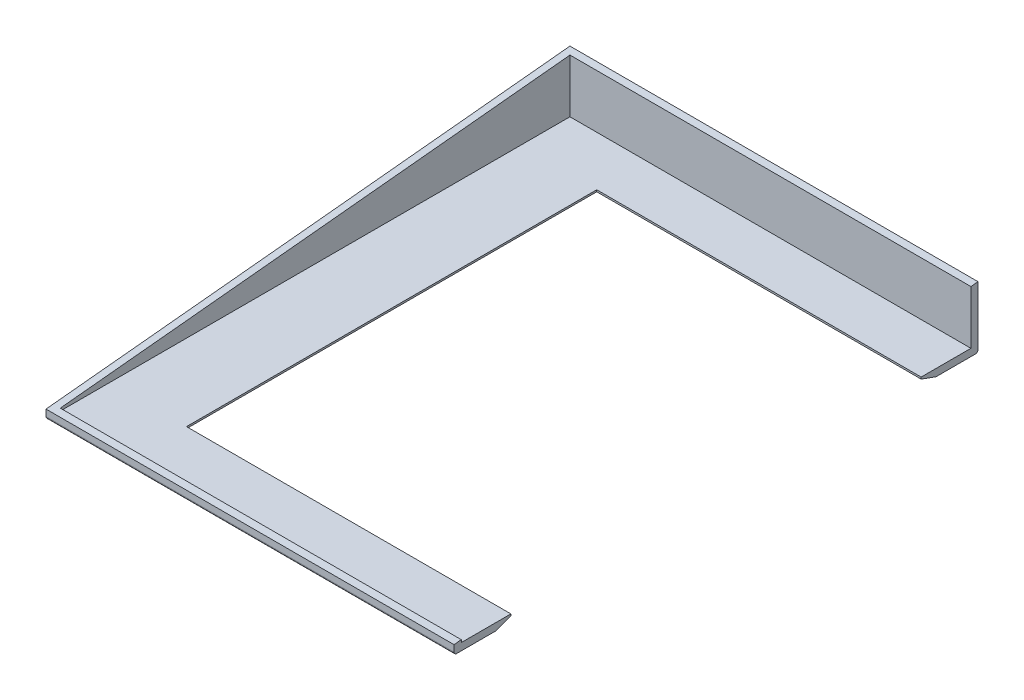
SolidWorks part; units mm, degrees
ref_plane "Alzado" through (0, 0, 0) normal (0, 0, 1) x (1, 0, 0)
ref_plane "Planta" through (0, 0, 0) normal (0, 1, 0) x (1, 0, 0)
ref_plane "Vista lateral" through (0, 0, 0) normal (1, 0, 0) x (0, 0, -1)
sketch "Croquis1" plane through (0, 0, 0) normal (0, 1, 0) x (1, 0, 0)
  line L1 (-110.2037, -69.6794) -> (110.2037, -69.6794)
  line L2 (-110.2037, -69.6794) -> (-110.2037, 69.6794)
  line L3 (-110.2037, 69.6794) -> (110.2037, 69.6794)
  line L4 (110.2037, -69.6794) -> (110.2037, 69.6794)
  line L5 (-110.2037, -69.6794) -> (110.2037, 69.6794) construction
  line L6 (-110.2037, 69.6794) -> (110.2037, -69.6794) construction
  line L7 (-90, -56.905) -> (90, -56.905)
  line L8 (-90, -56.905) -> (-90, 56.905)
  line L9 (-90, 56.905) -> (90, 56.905)
  line L10 (90, -56.905) -> (90, 56.905)
  line L11 (-90, -56.905) -> (90, 56.905) construction
  line L12 (-90, 56.905) -> (90, -56.905) construction
  point P0 (0, 0)
  point P5 (0, 0)
extrude "Saliente-Extruir1" add sketch "Croquis1" along normal blind 2
sketch "Croquis2" plane through (0, 2, 0) normal (0, 1, 0) x (1, 0, 0)
  line L1 (110.2037, -69.6794) -> (-110.2037, -69.6794)
  line L2 (110.2037, -69.6794) -> (110.2037, 69.6794)
  line L3 (110.2037, 69.6794) -> (-110.2037, 69.6794)
  line L4 (-110.2037, -69.6794) -> (-110.2037, 69.6794)
  line L5 (110.2037, -69.6794) -> (-110.2037, 69.6794) construction
  line L6 (110.2037, 69.6794) -> (-110.2037, -69.6794) construction
  point P0 (0, 0)
extrude "Extruir-Lámina3" add sketch "Croquis2" along normal blind 16.5 and the other way blind 2 thin thin type one direction wall 3
sketch "Croquis6" plane through (0, 18.5, 0) normal (0, 1, 0) x (1, 0, 0)
  line L9 (-111.2433, 70.719) -> (111.2037, 70.719)
  line L10 (-111.2433, 70.719) -> (-111.2433, -70.6794)
  line L11 (-111.2433, -70.6794) -> (111.2037, -70.6794)
  line L12 (111.2037, 70.719) -> (111.2037, -70.6794)
extrude "Cortar-Extruir2" cut sketch "Croquis6" against normal up to surface (16.5 mm away) up to face at (0, 2, 0)
sketch "Croquis7" plane through (-113.2037, 0, 0) normal (-1, 0, 0) x (0, 0, 1)
  line L0 (72.6794, 0) -> (72.6794, 2.5)
  line L1 (-72.6794, 0) -> (-72.6794, 17.0344)
  line L2 (-72.6794, 17.0344) -> (72.6794, 2.5)
  line L3 (56.905, 0) -> (-56.905, 0) construction
  line L6 (-72.6794, 17.0344) -> (-72.6794, 18.5)
  line L7 (-72.6794, 18.5) -> (72.6794, 18.5)
  line L8 (72.6794, 18.5) -> (72.6794, 2.5)
  line M7 (72.6794, 0) -> (72.6794, 18.5)
  line M8 (72.6794, 18.5) -> (-72.6794, 18.5)
  line M9 (-72.6794, 18.5) -> (-72.6794, 0)
  dimension "D1" = 5.71
  dimension "D2" = 2.5
extrude "Cortar-Extruir3" cut sketch "Croquis7" against normal up to surface (226.4074 mm away) contours L2 M9 M7 M8 up to face at (113.2037, 9.25, 0)
sketch "Croquis8" plane through (0, 0, -72.6794) normal (0, 0, -1) x (-1, 0, 0)
  line L0 (-113.2037, 17.0344) -> (-74.7037, 17.0344)
  line L1 (-113.2037, 17.0344) -> (113.2037, 17.0344) construction
  line L2 (-74.7037, 17.0344) -> (-74.7037, 9.0344)
  line L3 (-73.2037, 7.5344) -> (-35.2037, 7.5344)
  line L4 (-33.7037, 9.0344) -> (-33.7037, 17.0344)
  line L5 (-74.7037, 17.0344) -> (-33.7037, 17.0344)
  arc A0 (-35.2037, 7.5344) -> (-33.7037, 9.0344) centre (-35.2037, 9.0344) ccw
  arc A1 (-74.7037, 9.0344) -> (-73.2037, 7.5344) centre (-73.2037, 9.0344) ccw
  line M7 (113.2037, 17.0344) -> (-113.2037, 17.0344)
  dimension "D1" = 1.5
extrude "Cortar-Extruir4" cut sketch "Croquis8" against normal up to surface (1.9604 mm away) contours L2 A1 L3 A0 L4 M7 up to face at (-0.0198, 9.4192, -70.719)
fillet "Redondeo2" radius 0.7 10 edges at (33.7037, 12.9363, -70.719) (34.1431, 7.9737, -70.719) (54.2037, 7.5344, -70.719) (74.2644, 7.9737, -70.719) (33.7037, 13.0344, -72.6794) (34.1431, 7.9737, -72.6794) (54.2037, 7.5344, -72.6794) (74.2644, 7.9737, -72.6794) (74.7037, 12.9363, -70.719) (74.7037, 13.0344, -72.6794)
chamfer "Chaflán1" distance 1.5 angle 70 4 edges at (0, 0, -56.905) (-90, 0, 0) (0, 0, 56.905) (90, 0, 0)
fillet "Redondeo3" radius 0.7 4 edges at (0, 0, 72.6794) (-113.2037, 0, 0) (113.2037, 0, 0) (0, 0, -72.6794)
split "Partir1" trim tools "Vista lateral" bodies to split 112 resulting bodies 113
